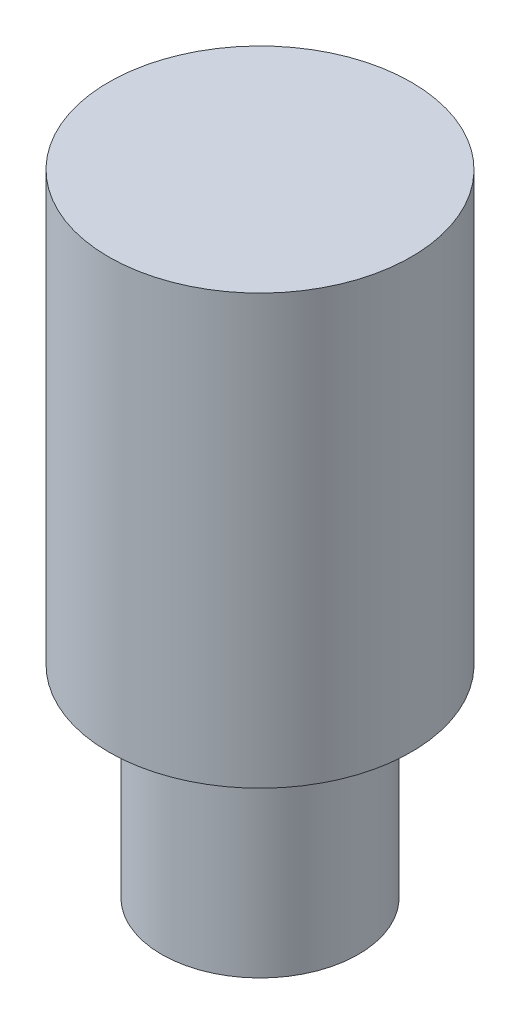
SolidWorks part; units mm, degrees
ref_plane "Front Plane" through (0, 0, 0) normal (0, 0, 1) x (1, 0, 0)
ref_plane "Top Plane" through (0, 0, 0) normal (0, 1, 0) x (1, 0, 0)
ref_plane "Right Plane" through (0, 0, 0) normal (1, 0, 0) x (0, 0, -1)
sketch "Sketch1" plane through (0, 0, 0) normal (0, 1, 0) x (1, 0, 0)
  circle A0 centre (0, 0) radius 1.95
  dimension "D1" = 3.9
extrude "Boss-Extrude1" add sketch "Sketch1" along normal blind 4
sketch "Sketch2" plane through (0, 4, 0) normal (0, 1, 0) x (1, 0, 0)
  circle A0 centre (0, 0) radius 3
  circle A1 centre (0, 0) radius 1.95 construction
  dimension "D1" = 6
extrude "Boss-Extrude2" add sketch "Sketch2" along normal blind 8.5
